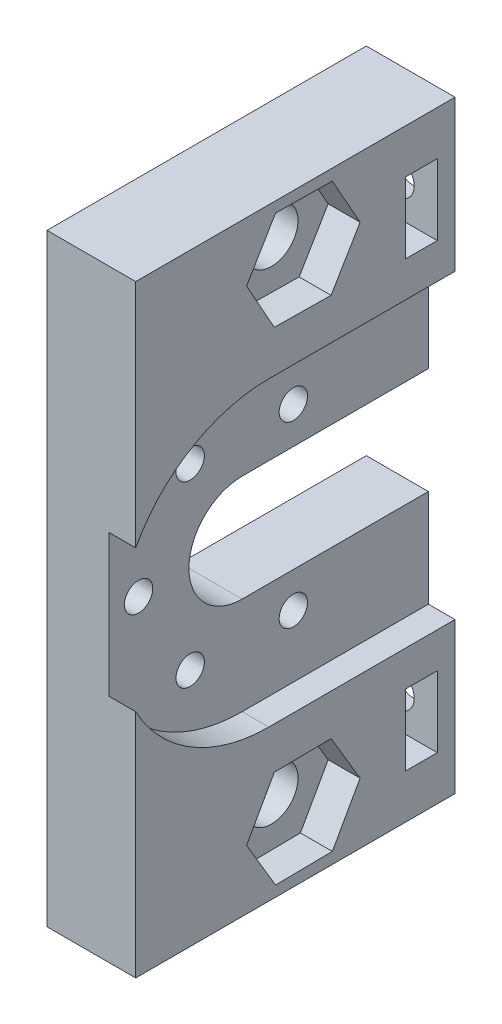
SolidWorks part; units mm, degrees
ref_plane "正面" through (0, 0, 0) normal (1, 0, 0) x (0, 1, 0)
ref_plane "平面" through (0, 0, 0) normal (0, 0, 1) x (0, 1, 0)
ref_plane "右側面" through (0, 0, 0) normal (0, 1, 0) x (-1, 0, 0)
sketch "ｽｹｯﾁ1" plane through (0, 0, 0) normal (1, 0, 0) x (0, 1, 0)
  line L0 (3, 0) -> (3, -10.5)
  line L1 (0, 5.7735) -> (-5, 2.8868) construction
  line L2 (-5, 2.8868) -> (-5, -2.8868) construction
  line L3 (-5, -2.8868) -> (0, -5.7735) construction
  line L4 (0, -5.7735) -> (5, -2.8868) construction
  line L5 (5, -2.8868) -> (5, 2.8868) construction
  line L6 (5, 2.8868) -> (0, 5.7735) construction
  line L7 (-17, 7.5) -> (17, 7.5)
  line L8 (-17, 7.5) -> (-17, -10.5)
  line L9 (-17, -10.5) -> (17, -10.5)
  line L10 (17, 7.5) -> (17, -10.5)
  line L11 (3, -10.5) -> (-3, -10.5)
  line L12 (-3, -10.5) -> (-3, 0)
  line L13 (-3, 0) -> (3, 0)
  circle A0 centre (0, 0) radius 0.75
  circle A1 centre (0, 0) radius 3
  circle A2 centre (0, 0) radius 5 construction
  circle A3 centre (-5, -2.8868) radius 0.8
  circle A4 centre (-5, 2.9296) radius 0.8
  circle A5 centre (0.0371, 5.8377) radius 0.8
  circle A6 centre (5.0742, 2.9296) radius 0.8
  circle A7 centre (5.0742, -2.8868) radius 0.8
  circle A8 centre (0.0371, -5.7949) radius 0.8
  circle A9 centre (0, 0) radius 8.5
  point P25 (0.0371, 0.0214)
  dimension "D1" = 1.5
  dimension "D2" = 6
  dimension "D3" = 10
  dimension "D4" = 1.6
  dimension "D6" = 17
  dimension "D7" = 10.5
  dimension "D8" = 18
  dimension "D9" = 17
  dimension "D10" = 34
  dimension "D5" = 6
extrude "ﾎﾞｽ - 押し出し5" add sketch "ｽｹｯﾁ1" against normal blind 5 contours A9 L7 L8 L9 L12 | L0 A9 L7 L12 A1 A7 A6 A5 A4 A3 | A9 L0 L9 L10 L7
sketch "ｽｹｯﾁ6" plane through (0, 0, 0) normal (1, 0, 0) x (0, 1, 0)
  line L0 (-8.5, 0) -> (-8.5, -10.5)
  line L1 (-17, -10.5) -> (-3, -10.5) construction
  line L2 (-8.5, -10.5) -> (8.5, -10.5)
  line L3 (3, -10.5) -> (17, -10.5) construction
  line L4 (8.5, -10.5) -> (8.5, 0)
  line L5 (8.5, 0) -> (-8.5, 0)
  circle A0 centre (0, 0) radius 8.5
  line M1 (-3, -10.5) -> (-3, 0)
  arc M2 (-3, 0) -> (3, 0) centre (0, 0) cw
  line M3 (3, 0) -> (3, -10.5)
  line M4 (3, -10.5) -> (17, -10.5)
  line M6 (17, 7.5) -> (-17, 7.5)
  line M8 (-17, -10.5) -> (-3, -10.5)
  circle M9 centre (5.0742, -2.8868) radius 0.8
  circle M10 centre (5.0742, 2.9296) radius 0.8
  circle M11 centre (0.0371, 5.8377) radius 0.8
  circle M12 centre (-5, 2.9296) radius 0.8
  circle M13 centre (-5, -2.8868) radius 0.8
  dimension "D1" = 17
extrude "ｶｯﾄ - 押し出し1" cut sketch "ｽｹｯﾁ6" against normal blind 1.5 contours L5 A0 M6 M2 M11 M12 M10 | L5 A0 M1 M13 | A0 L5 M3 M9 | A0 L4 M3 M4 | A0 L0 M8 M1
sketch "ｽｹｯﾁ7" plane through (-5, 0, 0) normal (-1, 0, 0) x (0, -1, 0)
  line L0 (0, 0) -> (0, 8.5494) construction
  line L1 (17, -10.5) -> (3, -10.5) construction
  line L2 (5.0623, -10.5) -> (-7.5408, -10.5) construction
  line L3 (5.0623, -10.5) -> (5.0623, -11.7) construction
  line L4 (5.0623, -11.7) -> (-7.5408, -11.7) construction
  line L5 (-7.5408, -10.5) -> (-7.5408, -11.7) construction
  line L6 (4.5077, -13.7) -> (2.1261, -13.7) construction
  circle A0 centre (0, 0) radius 3.25 construction
  circle A1 centre (-13.611, -1.95) radius 10.5 construction
  circle A3 centre (-13.611, -1.95) radius 11.75 construction
  circle A4 centre (0, 0) radius 8.5 construction
  circle A5 centre (-13.611, -1.95) radius 1.5
  circle A6 centre (13.611, -1.95) radius 1.5
  dimension "D1" = 6.5
  dimension "D2" = 21
  dimension "D3" = 23.5
  dimension "D4" = 17
  dimension "D5" = 1.2
  dimension "D6" = 10.5
  dimension "D8" = 3
  dimension "D7" = 2
extrude "ｶｯﾄ - 押し出し2" cut sketch "ｽｹｯﾁ7" against normal through all contours A6 | A5
sketch "ｽｹｯﾁ8" plane through (0, 0, 0) normal (1, 0, 0) x (0, 1, 0)
  line L0 (0, 0) -> (0, -2.816) construction
  line L13 (10.8192, -3.5139) -> (10.8607, -0.3142)
  line L14 (-10.8607, -0.3142) -> (-13.6525, 1.2497)
  line L15 (-13.6525, 1.2497) -> (-16.4028, -0.3861)
  line L16 (-16.4028, -0.3861) -> (-16.3613, -3.5858)
  line L17 (-16.3613, -3.5858) -> (-13.5695, -5.1497)
  line L18 (-13.5695, -5.1497) -> (-10.8192, -3.5139)
  line L19 (-10.8192, -3.5139) -> (-10.8607, -0.3142)
  line L20 (13.5695, -5.1497) -> (10.8192, -3.5139)
  line L21 (16.3613, -3.5858) -> (13.5695, -5.1497)
  line L22 (16.4028, -0.3861) -> (16.3613, -3.5858)
  line L23 (13.6525, 1.2497) -> (16.4028, -0.3861)
  line L24 (10.8607, -0.3142) -> (13.6525, 1.2497)
  circle A0 centre (-13.611, -1.95) radius 3.2 construction
extrude "ｶｯﾄ - 押し出し4" cut sketch "ｽｹｯﾁ8" against normal blind 1.8
sketch "ｽｹｯﾁ9" plane through (0, 0, -10.5) normal (0, 0, -1) x (1, 0, 0)
  line L0 (0, 17) -> (0, 8.5) construction
  line L1 (0, 12.5081) -> (-1.15, 14.5) construction
  line L2 (-1.15, 14.5) -> (-3.45, 14.5) construction
  line L3 (-3.45, 14.5) -> (-4.6, 12.5081) construction
  line L4 (-4.6, 12.5081) -> (-3.45, 10.5163) construction
  line L5 (-3.45, 10.5163) -> (-1.15, 10.5163) construction
  line L6 (-1.15, 10.5163) -> (0, 12.5081) construction
  line L8 (-5, 17) -> (0, 17) construction
  line L9 (-1.5, 8.5) -> (0, 8.5) construction
  line L10 (0, 0) -> (-7.4741, 0) construction
  circle A0 centre (-2.3, 12.5081) radius 1.9919 construction
  circle A1 centre (-2.3, 12.5081) radius 1
  circle A2 centre (-2.3, -12.5081) radius 1
  dimension "D2" = 2
  dimension "D1" = 4.6
  dimension "D3" = 2.5
  dimension "D4" = 2.0163
  dimension "D5" = 4.4919
extrude "ｶｯﾄ - 押し出し5" cut sketch "ｽｹｯﾁ9" against normal blind 1
sketch "ｽｹｯﾁ10" plane through (0, 0, 0) normal (1, 0, 0) x (0, 1, 0)
  line L0 (-17, 7.5) -> (-17, -10.5) construction
  line L1 (-14.5, -7.7) -> (-10.5, -7.7)
  line L2 (-14.5, -7.7) -> (-14.5, -9.5)
  line L3 (-14.5, -9.5) -> (-10.5, -9.5)
  line L4 (-10.5, -7.7) -> (-10.5, -9.5)
  line L5 (-17, -10.5) -> (-8.5, -10.5) construction
  line L6 (0, 0) -> (0, -3.2904) construction
  line L7 (14.5, -9.5) -> (10.5, -9.5)
  line L8 (10.5, -7.7) -> (10.5, -9.5)
  line L9 (14.5, -7.7) -> (10.5, -7.7)
  line L10 (14.5, -7.7) -> (14.5, -9.5)
  dimension "D1" = 2.5
  dimension "D2" = 4
  dimension "D3" = 1
  dimension "D4" = 1.8
extrude "ｶｯﾄ - 押し出し6" cut sketch "ｽｹｯﾁ10" against normal blind 4.6
sketch "ｽｹｯﾁ11" plane through (-5, 0, 0) normal (-1, 0, 0) x (0, -1, 0)
  line L0 (-16.0545, -10.5) -> (-24.2013, -10.5) construction
  line L2 (0, 0) -> (0, -13.1079) construction
  line L3 (-22.0311, -10.5) -> (22.0311, -10.5) construction
  line L4 (-22.0311, -10.5) -> (-22.0311, -11.7) construction
  line L5 (-22.0311, -11.7) -> (22.0311, -11.7) construction
  line L6 (22.0311, -10.5) -> (22.0311, -11.7) construction
  circle A0 centre (-13.611, -1.95) radius 12 construction
  circle A1 centre (13.611, -1.95) radius 12 construction
  point P13 (0, 0)
  point P15 (0, 0)
  point P16 (0, 0)
  dimension "D1" = 24
  dimension "D2" = 1.2
  dimension "D3" = 44.0622
